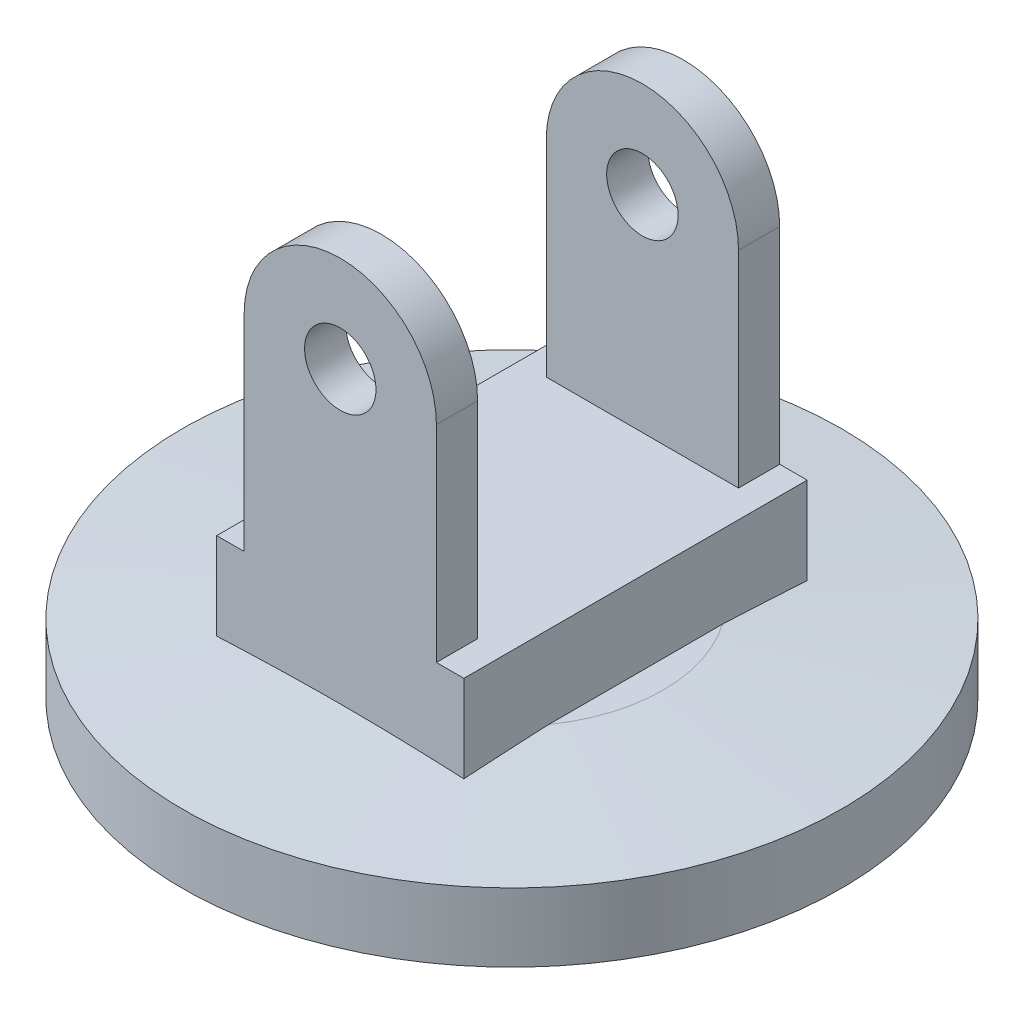
SolidWorks part; units mm, degrees
material "6061 Alloy"
ref_plane "Alzado" through (0, 0, 0) normal (0, 0, 1) x (1, 0, 0)
ref_plane "Planta" through (0, 0, 0) normal (0, 1, 0) x (1, 0, 0)
ref_plane "Vista lateral" through (0, 0, 0) normal (1, 0, 0) x (0, 0, -1)
ref_plane "Plane2" through (0, 0, -12.5) normal (0, 0, 1) x (1, 0, 0)
sketch "Sketch1" plane through (0, 0, -12.5) normal (0, 0, 1) x (1, 0, 0)
  line L0 (0, 0) -> (0, -16) construction
  line L1 (7, 0) -> (7, -16)
  line L2 (-7, 0) -> (-7, -16)
  arc A0 (7, 0) -> (-7, 0) centre (0, 0) ccw
  arc A1 (-7, -16) -> (7, -16) centre (0, -16) ccw
  point P3 (0, -8)
  point P8 (0, 0)
extrude "Oreja_anterior" add sketch "Sketch1" along normal blind 3
ref_plane "Plane3" through (0, 0, 9.5) normal (0, 0, 1) x (1, 0, 0)
sketch "Sketch2" plane through (0, 0, 9.5) normal (0, 0, 1) x (1, 0, 0)
  line L0 (0, 0) -> (0, -16) construction
  line L1 (7, 0) -> (7, -16)
  line L2 (-7, 0) -> (-7, -16)
  arc A0 (7, 0) -> (-7, 0) centre (0, 0) ccw
  arc A1 (-7, -16) -> (7, -16) centre (0, -16) ccw
  point P3 (0, -8)
  point P8 (0, 0)
extrude "Oreja_posterior" add sketch "Sketch2" along normal blind 3
sketch "Sketch3" plane through (0, 0, -12.5) normal (0, 0, 1) x (1, 0, 0)
  line L0 (-9, -23) -> (9, -23)
  line L1 (9, -23) -> (9, -15)
  line L2 (9, -15) -> (-9, -15)
  line L3 (-9, -15) -> (-9, -23)
extrude "Puente" add sketch "Sketch3" along normal blind 25
sketch "Sketch4" plane through (0, 0, 0) normal (0, 0, 1) x (1, 0, 0)
  line L0 (0, -21) -> (11, -21)
  line L1 (11, -21) -> (24, -22)
  line L2 (24, -22) -> (24, -27)
  line L3 (24, -27) -> (11, -27)
  line L4 (11, -27) -> (0, -27)
  line L5 (0, -27) -> (0, -21)
  line L6 (0, -31) -> (0, -17) construction
revolve "Brida_mano" add sketch "Sketch4" angle 360 about L6
sketch "Sketch5" plane through (0, 0, 0) normal (0, 0, 1) x (1, 0, 0)
  circle A0 centre (0, 0) radius 2.6
extrude "Agujero_eje_desviacion" cut sketch "Sketch5" against normal mid plane 2000
